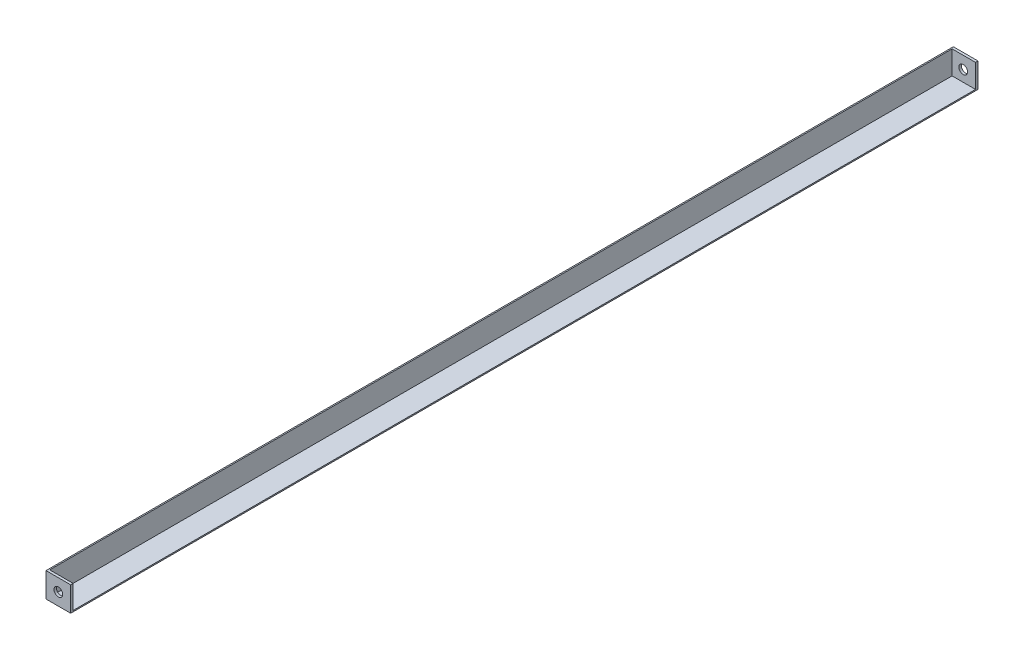
SolidWorks part; units mm, degrees
material "Galvanized Steel"
ref_plane "Front Plane" through (0, 0, 0) normal (0, 0, 1) x (1, 0, 0)
ref_plane "Top Plane" through (0, 0, 0) normal (0, 1, 0) x (1, 0, 0)
ref_plane "Right Plane" through (0, 0, 0) normal (1, 0, 0) x (0, 0, -1)
sketch "Sketch1" plane through (0, 0, 0) normal (0, 0, 1) x (1, 0, 0)
  line L0 (31.75, 1.5875) -> (1.5875, 1.5875)
  line L1 (0, 0) -> (31.75, 0)
  line L2 (0, 0) -> (0, 31.75)
  line L3 (0, 31.75) -> (1.5875, 31.75)
  line L4 (31.75, 0) -> (31.75, 1.5875)
  line L5 (1.5875, 1.5875) -> (1.5875, 31.75)
  dimension "D1" = 31.75
  dimension "D2" = 1.5875
extrude "Boss-Extrude1" add sketch "Sketch1" along normal mid plane 1168.4
sketch "Sketch2" plane through (0, 0, 0) normal (0, 0, 1) x (1, 0, 0)
  line L0 (31.75, 0) -> (31.75, 1.5875) construction
  line L1 (0, 0) -> (31.75, 0)
  line L2 (0, 0) -> (0, 31.75)
  line L3 (0, 31.75) -> (31.75, 31.75)
  line L4 (31.75, 0) -> (31.75, 31.75)
  circle A0 centre (15.875, 15.875) radius 5.588
  point P9 (15.875, 0)
  point P10 (0, 15.875)
  dimension "D1" = 11.176
extrude "Boss-Extrude2" add sketch "Sketch2" against normal blind 3.175 from offset 584.2
mirror "Mirror1" about plane through (0, 0, 0) normal (0, 0, 1) of "Boss-Extrude2"
